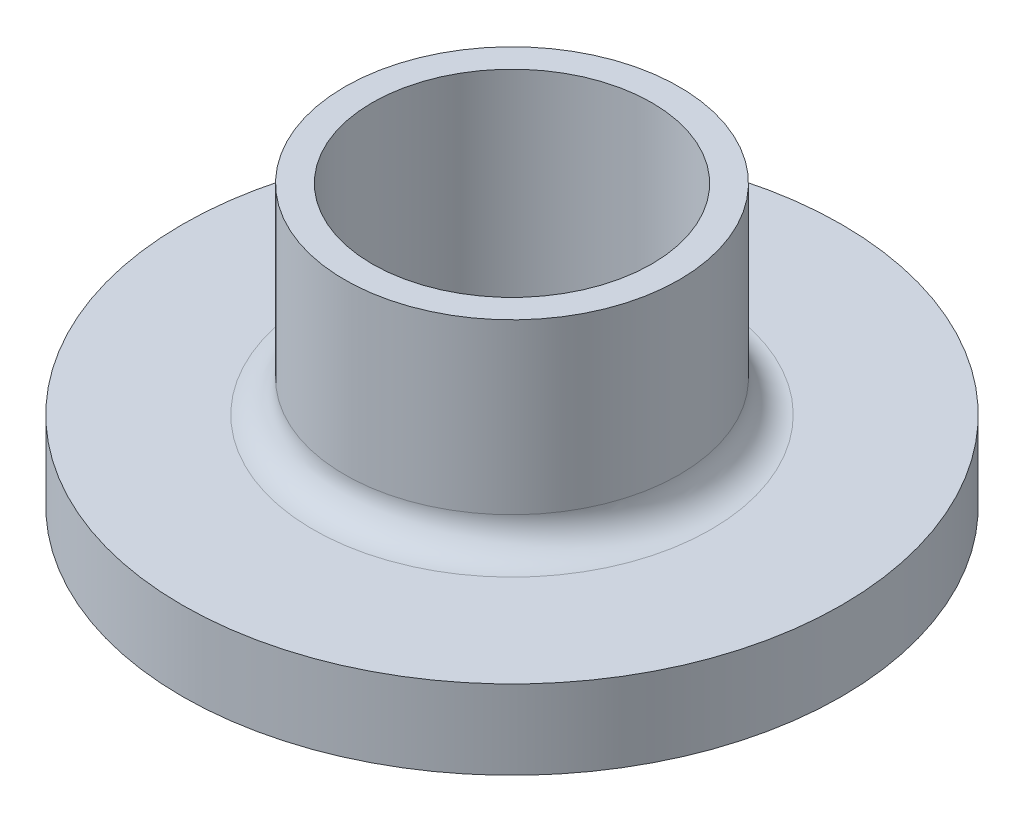
SolidWorks part; units mm, degrees
material "ABS"
ref_plane "Front Plane" through (0, 0, 0) normal (0, 0, 1) x (1, 0, 0)
ref_plane "Top Plane" through (0, 0, 0) normal (0, 1, 0) x (1, 0, 0)
ref_plane "Right Plane" through (0, 0, 0) normal (1, 0, 0) x (0, 0, -1)
sketch "Sketch1" plane through (0, 0, 0) normal (0, 0, 1) x (1, 0, 0)
  line L0 (0, 17.13) -> (0, -9.126) construction
  line L2 (3.3655, 0) -> (7.9375, 0)
  line L3 (7.9375, 0) -> (7.9375, 1.905)
  line L4 (7.9375, 1.905) -> (4.0259, 1.905)
  line L5 (4.0259, 1.905) -> (4.0259, 6.731)
  line L6 (4.0259, 6.731) -> (3.3655, 6.731)
  line L7 (3.3655, 6.731) -> (3.3655, 0)
  point P1 (0, 0)
  point P11 (4.3749, 0)
  point P12 (3.175, 0)
  point P13 (6.7945, 0)
  point P14 (3.3057, 0)
  dimension "D1" = 8.0518
  dimension "D2" = 6.731
  dimension "D3" = 4.826
  dimension "D4" = 15.875
  dimension "D5" = 1.905
revolve "Revolve1" add sketch "Sketch1" angle 360 about L0
fillet "Fillet1" radius 0.762 1 edges at (-4.0259, 1.905, 0)
